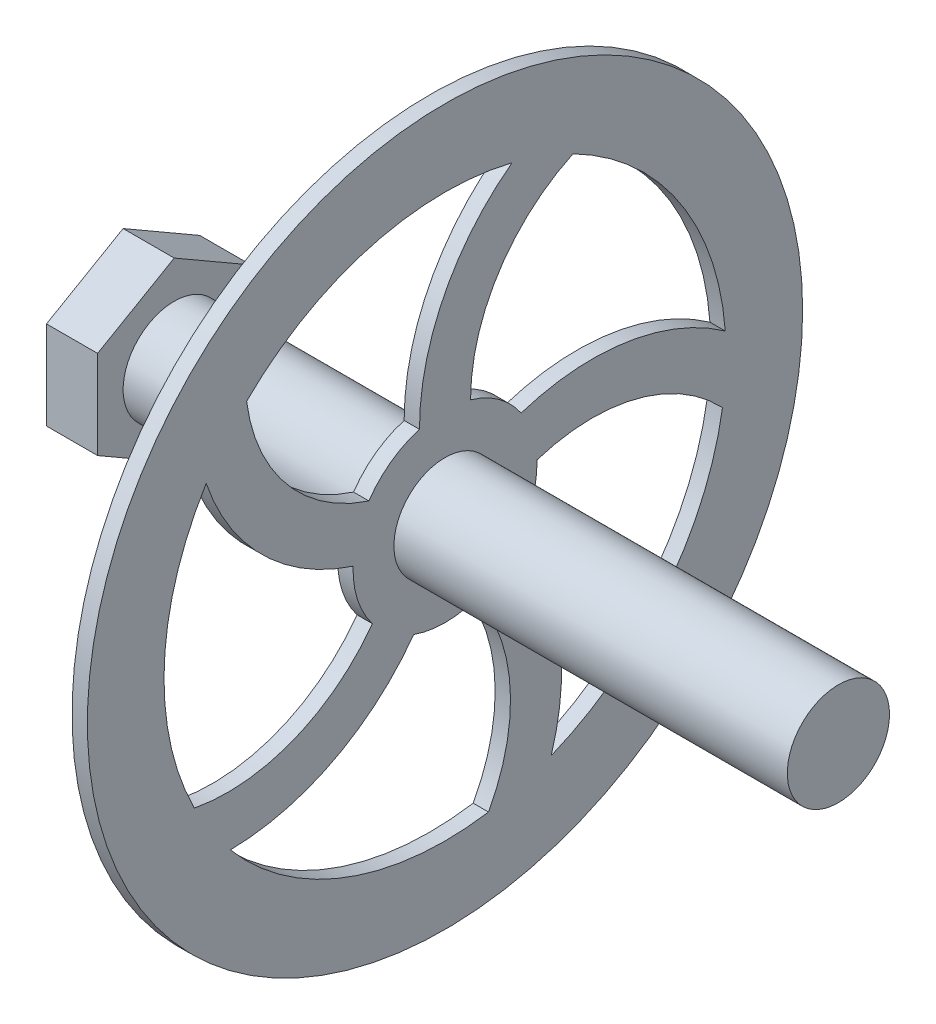
SolidWorks part; units mm, degrees
ref_plane "Front Plane" through (0, 0, 0) normal (0, 0, 1) x (1, 0, 0)
ref_plane "Top Plane" through (0, 0, 0) normal (0, 1, 0) x (1, 0, 0)
ref_plane "Right Plane" through (0, 0, 0) normal (1, 0, 0) x (0, 0, -1)
sketch "Sketch1" plane through (0, 0, 0) normal (1, 0, 0) x (0, 0, -1)
  circle A0 centre (0, 0) radius 10
  dimension "D1" = 20
extrude "Boss-Extrude1" add sketch "Sketch1" along normal blind 130
sketch "Sketch2" plane through (0, 0, 0) normal (-1, 0, 0) x (0, 0, 1)
  line L1 (0, 17.3205) -> (-15, 8.6603)
  line L2 (-15, 8.6603) -> (-15, -8.6603)
  line L3 (-15, -8.6603) -> (0, -17.3205)
  line L4 (0, -17.3205) -> (15, -8.6603)
  line L5 (15, -8.6603) -> (15, 8.6603)
  line L6 (15, 8.6603) -> (0, 17.3205)
  circle A0 centre (0, 0) radius 15 construction
  point P1 (0, 0)
  dimension "D1" = 30
extrude "Boss-Extrude2" add sketch "Sketch2" along normal blind 10
sketch "Sketch3" plane through (0, 0, 0) normal (1, 0, 0) x (0, 0, -1)
  line L0 (0, 0) -> (0, 55) construction
  circle A0 centre (0, 0) radius 70
  arc A1 (13.122, 53.4117) -> (-38.8291, 38.9526) centre (0, 0) ccw
  circle A2 centre (0, 0) radius 10 construction
  circle A3 centre (0, 0) radius 10
  arc A4 (-5, 17.2916) -> (-14.9002, 10.0987) centre (0, 0) ccw
  arc A5 (0, 17.3205) -> (40.1797, 57.3201) centre (40, 17.3205) cw construction
  arc A6 (5, 17.2916) -> (25.0472, 48.9657) centre (40, 17.3205) cw
  arc A7 (-5, 17.2916) -> (13.122, 53.4117) centre (40, 17.3205) cw
  arc A8 (-4.9949, 18.0004) -> (16.1752, 55.4962) centre (40, 17.3205) cw construction
  arc A9 (5.004, 17.8493) -> (21.4696, 47.0127) centre (40, 17.3205) cw construction
  arc A10 (0.0046, 17.9248) -> (18.8224, 51.2544) centre (40, 17.3205) cw construction
  circle A11 centre (0, 0) radius 55 construction
  arc A12 (17.9904, 0.5881) -> (54.3091, -8.6901) centre (28.8335, -32.6899) cw
  arc A13 (14.9002, 10.0987) -> (54.8525, 4.0253) centre (28.8335, -32.6899) cw
  arc A14 (6.1187, -16.9281) -> (8.5176, -54.3365) centre (-22.1799, -37.524) cw
  arc A15 (14.2088, -11.0503) -> (20.7787, -50.9239) centre (-22.1799, -37.524) cw
  arc A16 (-14.2088, -11.0503) -> (-49.0449, -24.8916) centre (-42.5414, 9.4988) cw
  arc A17 (-6.1187, -16.9281) -> (-42.0106, -35.498) centre (-42.5414, 9.4988) cw
  arc A18 (-14.9002, 10.0987) -> (-38.8291, 38.9526) centre (-4.1121, 43.3946) cw
  arc A19 (-17.9904, 0.5881) -> (-46.7426, 28.9849) centre (-4.1121, 43.3946) cw
  arc A20 (-17.9904, 0.5881) -> (-14.2088, -11.0503) centre (0, 0) ccw
  arc A21 (-46.7426, 28.9849) -> (-49.0449, -24.8916) centre (0, 0) ccw
  arc A22 (-42.0106, -35.498) -> (8.5176, -54.3365) centre (0, 0) ccw
  arc A23 (20.7787, -50.9239) -> (54.3091, -8.6901) centre (0, 0) ccw
  arc A24 (-6.1187, -16.9281) -> (6.1187, -16.9281) centre (0, 0) ccw
  arc A25 (14.2088, -11.0503) -> (17.9904, 0.5881) centre (0, 0) ccw
  arc A26 (14.9002, 10.0987) -> (5, 17.2916) centre (0, 0) ccw
  arc A27 (54.8525, 4.0253) -> (25.0472, 48.9657) centre (0, 0) ccw
  point P25 (52.5968, 16.0804)
  point P52 (0, 0)
  dimension "D1" = 15
  dimension "D2" = 8
  dimension "D3" = 140
  dimension "D4" = 5
  dimension "D6" = 40
  dimension "D7" = 5
  dimension "D5" = 5
extrude "Boss-Extrude3" add sketch "Sketch3" along normal blind 3 from offset 50 separate body
